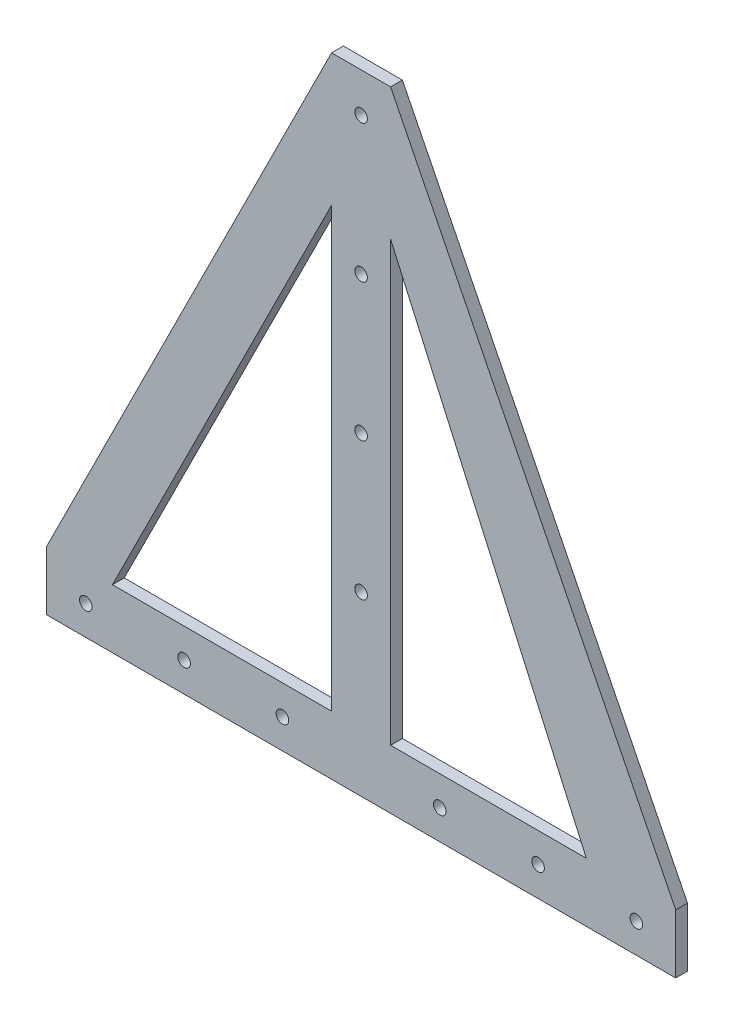
SolidWorks part; units mm, degrees
ref_plane "Front Plane" through (0, 0, 0) normal (0, 0, 1) x (1, 0, 0)
ref_plane "Top Plane" through (0, 0, 0) normal (0, 1, 0) x (1, 0, 0)
ref_plane "Right Plane" through (0, 0, 0) normal (1, 0, 0) x (0, 0, -1)
sketch "Sketch1" plane through (0, 0, 0) normal (0, 0, 1) x (1, 0, 0)
  line L0 (0, 15) -> (72.5, 160)
  line L1 (0, 0) -> (160, 0)
  line L2 (0, 0) -> (0, 15)
  line L3 (0, 7.5) -> (160, 7.5) construction
  line L4 (160, 0) -> (160, 15)
  line L5 (72.5, 160) -> (87.5, 160)
  line L6 (87.5, 160) -> (160, 15)
  line L7 (80, 0) -> (80, 160) construction
  line L8 (-25, 7.5) -> (135, 7.5) construction
  line L9 (-50, 7.5) -> (110, 7.5) construction
  line L10 (72.5, 126.459) -> (72.5, 15)
  line L11 (72.5, 15) -> (16.7705, 15)
  line L12 (16.7705, 15) -> (72.5, 126.459)
  line L13 (47.627, 76.713) -> (34.2106, 83.4212) construction
  line L14 (50.5792, 15) -> (50.5792, 0) construction
  line L15 (87.5, 15) -> (137.2715, 15)
  line L16 (87.5, 126.459) -> (87.5, 15)
  line L17 (137.2715, 15) -> (87.5, 126.459)
  line L18 (72.5, 103.3061) -> (87.5, 103.3061) construction
  circle A0 centre (150, 7.5) radius 1.6
  circle A1 centre (125, 7.5) radius 1.6
  circle A2 centre (100, 7.5) radius 1.6
  circle A3 centre (10, 7.5) radius 1.6
  circle A4 centre (35, 7.5) radius 1.6
  circle A5 centre (60, 7.5) radius 1.6
  circle A6 centre (80, 150) radius 1.6
  circle A7 centre (80, 115) radius 1.6
  circle A8 centre (80, 80) radius 1.6
  circle A9 centre (80, 45) radius 1.6
  point P5 (80, 160)
  dimension "D5" = 3.2
  dimension "D8" = 3.2
  dimension "D1" = 160
  dimension "D2" = 160
  dimension "D3" = 15
  dimension "D4" = 15
  dimension "D6" = 10
  dimension "D9" = 10
extrude "Boss-Extrude1" add sketch "Sketch1" along normal blind 3
